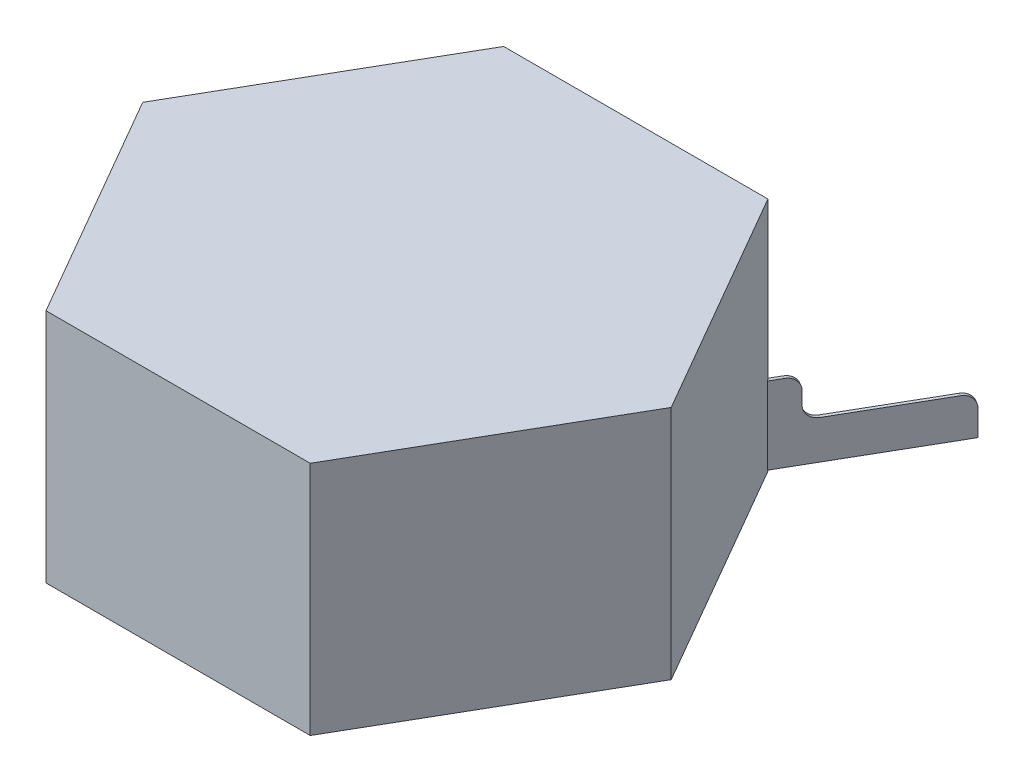
SolidWorks part; units mm, degrees
ref_plane "Front Plane" through (0, 0, 0) normal (0, 0, 1) x (1, 0, 0)
ref_plane "Top Plane" through (0, 0, 0) normal (0, 1, 0) x (1, 0, 0)
ref_plane "Right Plane" through (0, 0, 0) normal (1, 0, 0) x (0, 0, -1)
sketch "Sketch1" plane through (0, 6.35, 0) normal (0, 1, 0) x (1, 0, 0)
  line L2 (3314.7771, 4460.0678) -> (2827.4146, 3615.9312) construction
  line L3 (2827.4146, 5362.9445) -> (3314.7771, 4518.8079) construction
  line L4 (1801.8192, 5392.3146) -> (2776.5442, 5392.3146) construction
  line L5 (1750.9488, 3615.9312) -> (1263.5863, 4460.0678) construction
  line L6 (1263.5863, 4518.8079) -> (1750.9488, 5362.9445) construction
  line L7 (1767.9056, 3586.5612) -> (2810.4578, 3586.5612)
  line L9 (3331.7339, 4489.4379) -> (2810.4578, 3586.5612)
  line L10 (2810.4578, 5392.3146) -> (3331.7339, 4489.4379)
  line L11 (1767.9056, 5392.3146) -> (2810.4578, 5392.3146)
  line L12 (1767.9056, 3586.5612) -> (1246.6295, 4489.4379)
  line L13 (1246.6295, 4489.4379) -> (1767.9056, 5392.3146)
extrude "Boss-Extrude1" add sketch "Sketch1" along normal up to surface (930.275 mm away)
sketch "Sketch2" plane through (-232.5966, 0, -134.2897) normal (-0.866, 0, -0.5) x (-0.5, 0, 0.866)
  line L6 (-6222.9291, 167.3784) -> (-6629.3291, 167.3784)
  line L7 (-6680.1291, 116.5784) -> (-6680.1291, 14.9784)
  line L8 (-6680.1291, 14.9784) -> (-6070.5291, 14.9784)
  line L9 (-6070.5291, 14.9784) -> (-6070.5291, 319.7784)
  line L10 (-6070.5291, 319.7784) -> (-6121.3291, 319.7784)
  line L11 (-6172.1291, 268.9784) -> (-6172.1291, 218.1784)
  line L12 (-6222.9291, 167.3784) -> (-6629.3291, 167.3784)
  line L13 (-6680.1291, 116.5784) -> (-6680.1291, 14.9784)
  line L14 (-6680.1291, 14.9784) -> (-6070.5291, 14.9784)
  line L15 (-6070.5291, 14.9784) -> (-6070.5291, 319.7784)
  line L16 (-6070.5291, 319.7784) -> (-6121.3291, 319.7784)
  line L17 (-6172.1291, 268.9784) -> (-6172.1291, 218.1784)
  arc A3 (-6222.9291, 167.3784) -> (-6172.1291, 218.1784) centre (-6222.9291, 218.1784) ccw
  arc A4 (-6629.3291, 167.3784) -> (-6680.1291, 116.5784) centre (-6629.3291, 116.5784) ccw
  arc A5 (-6121.3291, 319.7784) -> (-6172.1291, 268.9784) centre (-6121.3291, 268.9784) ccw
  arc A6 (-6222.9291, 167.3784) -> (-6172.1291, 218.1784) centre (-6222.9291, 218.1784) ccw
  arc A7 (-6629.3291, 167.3784) -> (-6680.1291, 116.5784) centre (-6629.3291, 116.5784) ccw
  arc A8 (-6121.3291, 319.7784) -> (-6172.1291, 268.9784) centre (-6121.3291, 268.9784) ccw
  dimension "D1" = 0
extrude "Boss-Extrude2" add sketch "Sketch2" against normal up to surface (12.7 mm away)
sketch "Sketch3" plane through (3655.3706, 0, -2110.4292) normal (-0.866, 0, 0.5) x (0.5, 0, 0.866)
  line L6 (-3933.7474, 167.3784) -> (-4340.1474, 167.3784)
  line L7 (-4390.9474, 116.5784) -> (-4390.9474, 14.9784)
  line L8 (-4390.9474, 14.9784) -> (-3781.3474, 14.9784)
  line L9 (-3781.3474, 14.9784) -> (-3781.3474, 319.7784)
  line L10 (-3781.3474, 319.7784) -> (-3832.1474, 319.7784)
  line L11 (-3882.9474, 268.9784) -> (-3882.9474, 218.1784)
  line L12 (-3933.7474, 167.3784) -> (-4340.1474, 167.3784)
  line L13 (-4390.9474, 116.5784) -> (-4390.9474, 14.9784)
  line L14 (-4390.9474, 14.9784) -> (-3781.3474, 14.9784)
  line L15 (-3781.3474, 14.9784) -> (-3781.3474, 319.7784)
  line L16 (-3781.3474, 319.7784) -> (-3832.1474, 319.7784)
  line L17 (-3882.9474, 268.9784) -> (-3882.9474, 218.1784)
  arc A3 (-3933.7474, 167.3784) -> (-3882.9474, 218.1784) centre (-3933.7474, 218.1784) ccw
  arc A4 (-4340.1474, 167.3784) -> (-4390.9474, 116.5784) centre (-4340.1474, 116.5784) ccw
  arc A5 (-3832.1474, 319.7784) -> (-3882.9474, 268.9784) centre (-3832.1474, 268.9784) ccw
  arc A6 (-3933.7474, 167.3784) -> (-3882.9474, 218.1784) centre (-3933.7474, 218.1784) ccw
  arc A7 (-4340.1474, 167.3784) -> (-4390.9474, 116.5784) centre (-4340.1474, 116.5784) ccw
  arc A8 (-3832.1474, 319.7784) -> (-3882.9474, 268.9784) centre (-3832.1474, 268.9784) ccw
  dimension "D1" = 0
extrude "Boss-Extrude3" add sketch "Sketch3" against normal up to surface (12.7 mm away)
